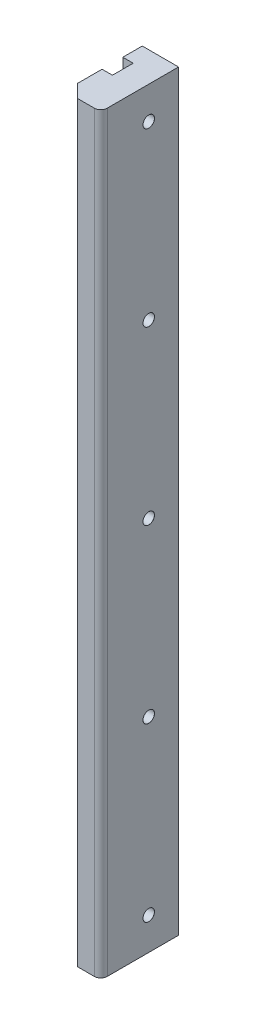
SolidWorks part; units mm, degrees
ref_plane "Front Plane" through (0, 0, 0) normal (0, 0, 1) x (1, 0, 0)
ref_plane "Top Plane" through (0, 0, 0) normal (0, 1, 0) x (1, 0, 0)
ref_plane "Right Plane" through (0, 0, 0) normal (1, 0, 0) x (0, 0, -1)
sketch "Sketch1" plane through (0, 0, 0) normal (0, 1, 0) x (1, 0, 0)
  line L0 (-28, 27.5) -> (0, 27.5)
  line L5 (0, 27.5) -> (0, -27.5)
  line L6 (-5, -32.5) -> (-18, -32.5)
  line L7 (-28, -22.5) -> (-28, -3.5)
  line L8 (-28, -3.5) -> (-20, -3.5)
  line L9 (-20, -3.5) -> (-20, 12.5)
  line L10 (-20, 12.5) -> (-28, 12.5)
  line L11 (-28, 12.5) -> (-28, 27.5)
  line L12 (-18, -32.5) -> (-28, -22.5)
  arc A0 (0, -27.5) -> (-5, -32.5) centre (-5, -27.5) cw
  point P4 (-28, -32.5)
  point P5 (0, 0)
  point P14 (0, -32.5)
  dimension "D8" = 5
  dimension "D1" = 60
  dimension "D2" = 28
  dimension "D4" = 8
  dimension "D5" = 16
  dimension "D6" = 15
  dimension "D7" = 19
extrude "Boss-Extrude1" add sketch "Sketch1" along normal blind 580
sketch "Sketch2" plane through (0, 0, 0) normal (1, 0, 0) x (0, 0, -1)
  line L0 (4.5, -31.6952) -> (27.5, -31.6952) construction
  line L2 (4.5, -31.6952) -> (4.5, 290) construction
  line L3 (27.5, 580) -> (27.5, 0) construction
  dimension "D1" = 23
sketch "Sketch4" plane through (0, 0, 0) normal (1, 0, 0) x (0, 0, -1)
  line L0 (4.5, -31.6952) -> (4.5, 290) construction
  line L1 (-27.5, 0) -> (27.5, 0) construction
  line L2 (-27.5, 290) -> (27.5, 290) construction
  line L3 (-27.5, 580) -> (-27.5, 0) construction
  line L4 (27.5, 580) -> (27.5, 0) construction
  point P0 (4.5, 25)
  point P1 (4.5, 157.5)
  point P6 (4.5, 290)
  point P14 (4.5, 422.5)
  point P15 (4.5, 555)
  dimension "D1" = 25
  dimension "D2" = 132.5
hole_wizard "Tap Drill for M10x1.25 Tap1" positions "3DSketch2" profile "Sketch5" hole size "M10x1.25" standard "ISO" end condition through all
sketch3d "3DSketch2"
  point P0 (0, 25, -4.5)
  point P3 (0, 157.5, -4.5)
  point P6 (0, 290, -4.5)
  point P9 (0, 422.5, -4.5)
  point P12 (0, 555, -4.5)
sketch "Sketch5" plane through (0, 25, -4.5) normal (0, 1, 0) x (0, 0, -1)
  line L0 (0, 0) -> (0, 28)
  line L1 (0, 28) -> (4.4, 28)
  line L2 (4.4, 28) -> (4.4, 0.025)
  line L3 (4.4, 0.025) -> (4.425, 0)
  line L5 (4.425, 0) -> (0, 0)
  line L6 (-4.4, 0.025) -> (-4.425, 0) construction
  line L11 (0, -6.35) -> (0, 107.95) construction
  dimension "Thru Hole Dia." = 8.8
  dimension "Thru Hole Depth" = 28
  dimension "Near C'Sink Dia." = 8.85
  dimension "Near C'Sink Angle" = 90
